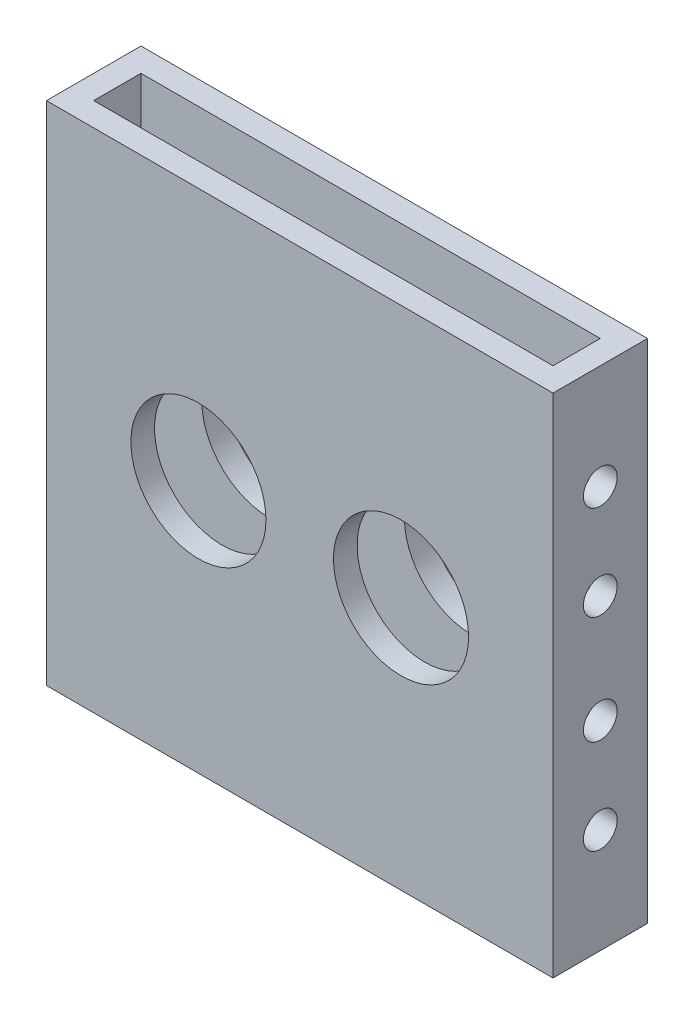
SolidWorks part; units mm, degrees
material "ABS"
ref_plane "Front Plane" through (0, 0, 0) normal (0, 0, 1) x (1, 0, 0)
ref_plane "Top Plane" through (0, 0, 0) normal (0, 1, 0) x (1, 0, 0)
ref_plane "Right Plane" through (0, 0, 0) normal (1, 0, 0) x (0, 0, -1)
sketch "Sketch1" plane through (0, 0, 0) normal (0, 0, 1) x (1, 0, 0)
  line L1 (-47.625, -47.625) -> (47.625, -47.625)
  line L2 (-47.625, -47.625) -> (-47.625, 47.625)
  line L3 (-47.625, 47.625) -> (47.625, 47.625)
  line L4 (47.625, -47.625) -> (47.625, 47.625)
  line L5 (-47.625, -47.625) -> (47.625, 47.625) construction
  line L6 (-47.625, 47.625) -> (47.625, -47.625) construction
  point P0 (0, 0)
  dimension "D1" = 95.25
  dimension "D2" = 95.25
extrude "Boss-Extrude1" add sketch "Sketch1" against normal blind 17.78
sketch "Sketch2" plane through (0, 47.625, 0) normal (0, 1, 0) x (1, 0, 0)
  line L8 (-43.18, 4.445) -> (43.18, 4.445)
  line L9 (43.18, 4.445) -> (43.18, 13.335)
  line L10 (43.18, 13.335) -> (-43.18, 13.335)
  line L11 (-43.18, 13.335) -> (-43.18, 4.445)
  line L12 (-43.18, 4.445) -> (43.18, 4.445)
  line L13 (43.18, 4.445) -> (43.18, 13.335)
  line L14 (43.18, 13.335) -> (-43.18, 13.335)
  line L15 (-43.18, 13.335) -> (-43.18, 4.445)
  dimension "D1" = 4.445
extrude "Cut-Extrude1" cut sketch "Sketch2" against normal through all
sketch "Sketch3" plane through (0, 0, 0) normal (0, 0, 1) x (1, 0, 0)
  line L0 (0, 0) -> (0, 47.625) construction
  line L1 (47.625, 47.625) -> (-47.625, 47.625) construction
  line L2 (-19.05, 0) -> (19.05, 0)
  circle A0 centre (19.05, 0) radius 12.7
  circle A1 centre (-19.05, 0) radius 12.7
  point P8 (-5.873, 2.1976)
  point P10 (0, 23.8125)
  point P11 (-5.873, 2.1976)
  dimension "D1" = 38.1
extrude "Cut-Extrude2" cut sketch "Sketch3" against normal through all
sketch "Sketch4" plane through (47.625, 0, 0) normal (1, 0, 0) x (0, 0, -1)
  line L0 (0, 0) -> (17.78, 0) construction
  line L1 (0, -47.625) -> (0, 47.625) construction
  line L2 (17.78, -47.625) -> (17.78, 47.625) construction
  line L3 (8.89, -10.16) -> (8.89, 10.16)
  line L5 (8.89, -10.16) -> (8.89, -27.94) construction
  line L6 (8.89, 10.16) -> (8.89, 27.94) construction
  circle A0 centre (8.89, 10.16) radius 3.175
  circle A1 centre (8.89, -10.16) radius 3.175
  circle A2 centre (8.89, -27.94) radius 3.175
  circle A3 centre (8.89, 27.94) radius 3.175
  point P9 (8.89, 0)
  dimension "D2" = 6.35
  dimension "D4" = 6.35
  dimension "D1" = 20.32
  dimension "D3" = 17.78
extrude "Cut-Extrude3" cut sketch "Sketch4" against normal through all
